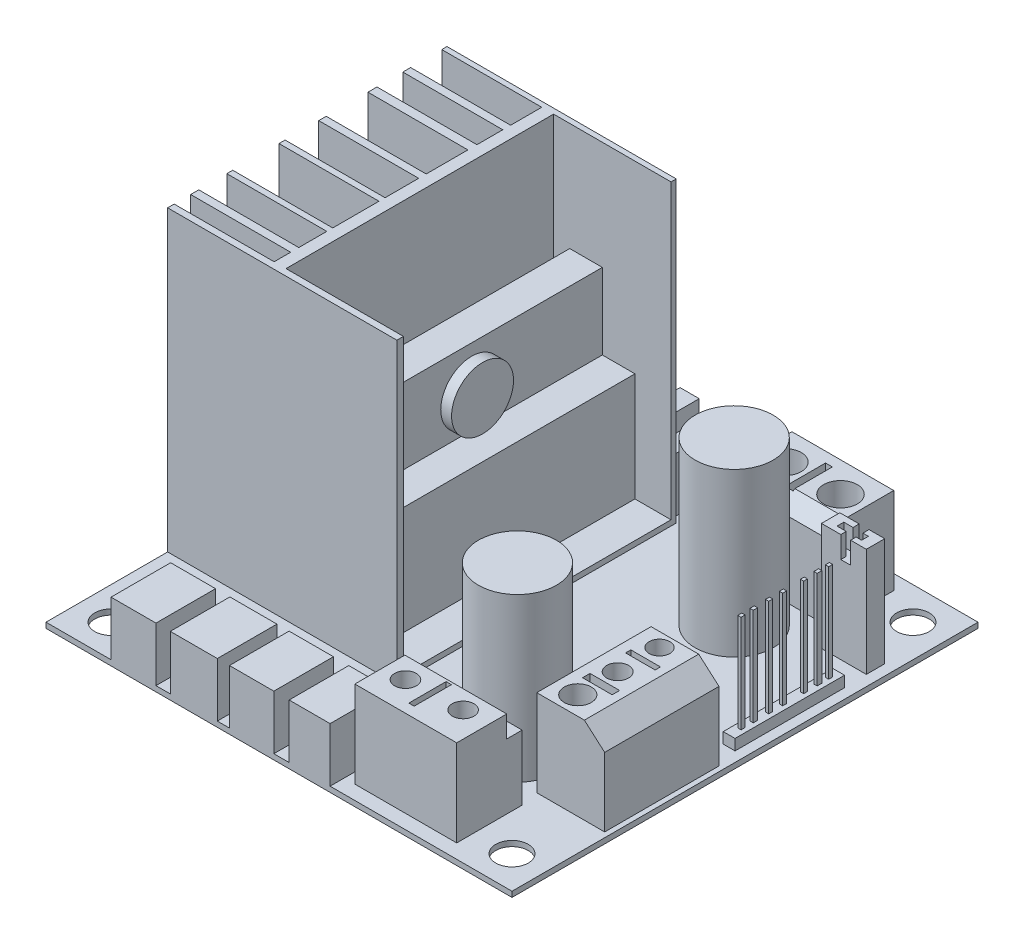
SolidWorks part; units mm, degrees
ref_plane "前视基准面" through (0, 0, 0) normal (0, 0, 1) x (1, 0, 0)
ref_plane "上视基准面" through (0, 0, 0) normal (0, 1, 0) x (1, 0, 0)
ref_plane "右视基准面" through (0, 0, 0) normal (1, 0, 0) x (0, 0, -1)
sketch "草图4" plane through (0, 0, 0) normal (0, 1, 0) x (1, 0, 0)
  line L1 (-21.5, 21.5) -> (21.5, 21.5)
  line L2 (-21.5, 21.5) -> (-21.5, -21.5)
  line L3 (-21.5, -21.5) -> (21.5, -21.5)
  line L4 (21.5, 21.5) -> (21.5, -21.5)
extrude "凸台-拉伸2" add sketch "草图4" along normal blind 0.5
sketch "草图5" plane through (0, 0.5, 0) normal (0, 1, 0) x (1, 0, 0)
  line L0 (-21.5, 21.5) -> (-21.5, -21.5) construction
  line L1 (-21.5, 15.5) -> (-4.3117, 15.5)
  line L2 (-21.5, 15.5) -> (-21.5, -9.2413)
  line L3 (-21.5, -9.2413) -> (-4.3117, -9.2413)
  line L4 (-4.3117, 15.5) -> (-4.3117, -9.2413)
  line L5 (-21.5, -21.5) -> (21.5, -21.5) construction
  line L6 (21.5, 21.5) -> (-21.5, 21.5) construction
  line L7 (21.5, -21.5) -> (21.5, 21.5) construction
  circle A1 centre (-18.5, -18.5) radius 1.5
  circle A2 centre (18.5, 18.5) radius 1.5
  circle A3 centre (-18.5, 18.5) radius 1.5
  circle A4 centre (18.5, -18.5) radius 1.5
  point P14 (18.5, -18.5)
  point P17 (0, 0)
  point P19 (-17.7173, -13.8255)
  dimension "D1" = 37
  dimension "D3" = 3
  dimension "D2" = 37
  dimension "D4" = 3
  dimension "D5" = 3
  dimension "D6" = 3
  dimension "D7" = 3
  dimension "D8" = 3
  dimension "D9" = 3
extrude "切除-拉伸2" cut sketch "草图5" against normal through all contours A3 | A2 | A4 | A1
sketch "草图7" plane through (0, 0.5, 0) normal (0, 1, 0) x (1, 0, 0)
  line L0 (-21.5, 21.5) -> (-21.5, -21.5) construction
  line L1 (-21.5, 15.5) -> (-0.3449, 15.5)
  line L2 (-21.5, 15.5) -> (-21.5, -10.2761)
  line L3 (-21.5, -10.2761) -> (-0.3449, -10.2761)
  line L4 (-0.3449, 15.5) -> (-0.3449, -10.2761)
extrude "凸台-拉伸5" add sketch "草图7" along normal blind 27.5
sketch "草图8" plane through (0, 0.5, 0) normal (0, 1, 0) x (1, 0, 0)
  line L0 (21.5, 21.5) -> (-21.5, 21.5) construction
  line L1 (-15.5, 21.5) -> (4.7141, 21.5)
  line L2 (-15.5, 21.5) -> (-15.5, 16)
  line L3 (-15.5, 16) -> (4.7141, 16)
  line L4 (4.7141, 21.5) -> (4.7141, 16)
sketch "草图9" plane through (0, 0.5, 0) normal (0, 1, 0) x (1, 0, 0)
  line L0 (-21.5, -21.5) -> (21.5, -21.5) construction
  line L1 (-15.5, -21.5) -> (4.7141, -21.5)
  line L2 (-15.5, -21.5) -> (-15.5, -16)
  line L3 (-15.5, -16) -> (4.7141, -16)
  line L4 (4.7141, -21.5) -> (4.7141, -16)
extrude "凸台-拉伸8" add sketch "草图8" along normal blind 5
sketch "草图11" plane through (0, 0.5, 0) normal (0, 1, 0) x (1, 0, 0)
extrude "凸台-拉伸9" add sketch "草图9" along normal blind 5
sketch "草图13" plane through (0, 0.5, 0) normal (0, 1, 0) x (1, 0, 0)
  line L1 (5.6914, -14.1566) -> (15.0908, -14.1566)
  line L2 (5.6914, -14.1566) -> (5.6914, -20.193)
  line L3 (5.6914, -20.193) -> (15.0908, -20.193)
  line L4 (15.0908, -14.1566) -> (15.0908, -20.193)
extrude "凸台-拉伸10" add sketch "草图13" along normal blind 8
sketch "草图14" plane through (0, 0.5, 0) normal (0, 1, 0) x (1, 0, 0)
  line L1 (5.6914, 14.2429) -> (15.0908, 14.2429)
  line L2 (5.6914, 14.2429) -> (5.6914, 20.1355)
  line L3 (5.6914, 20.1355) -> (15.0908, 20.1355)
  line L4 (15.0908, 14.2429) -> (15.0908, 20.1355)
extrude "凸台-拉伸11" add sketch "草图14" along normal blind 8
sketch "草图15" plane through (0, 0.5, 0) normal (0, 1, 0) x (1, 0, 0)
  circle A0 centre (10.5, -10) radius 3.6
extrude "凸台-拉伸13" add sketch "草图15" along normal blind 15
sketch "草图16" plane through (0, 0.5, 0) normal (0, 1, 0) x (1, 0, 0)
  circle A0 centre (10.5, 10) radius 3.6
extrude "凸台-拉伸14" add sketch "草图16" along normal blind 15 contours A0
sketch "草图19" plane through (0, 0.5, 0) normal (0, 1, 0) x (1, 0, 0)
  line L1 (14.7746, -1.9402) -> (21.0409, -1.9402)
  line L2 (14.7746, -1.9402) -> (14.7746, -12.4895)
  line L3 (14.7746, -12.4895) -> (21.0409, -12.4895)
  line L4 (21.0409, -1.9402) -> (21.0409, -12.4895)
extrude "凸台-拉伸15" add sketch "草图19" along normal blind 8
sketch "草图20" plane through (0, 0.5, 0) normal (0, 1, 0) x (1, 0, 0)
  line L1 (16.3843, 13.8692) -> (20.5235, 13.8692)
  line L2 (16.3843, 13.8692) -> (16.3843, 12.1733)
  line L3 (16.3843, 12.1733) -> (20.5235, 12.1733)
  line L4 (20.5235, 13.8692) -> (20.5235, 12.1733)
extrude "凸台-拉伸16" add sketch "草图20" along normal blind 10
sketch "草图21" plane through (0, 0.5, 0) normal (0, 1, 0) x (1, 0, 0)
  line L1 (20.581, 10.1037) -> (19.4887, 10.1037)
  line L2 (20.581, 10.1037) -> (20.581, 0)
  line L3 (20.581, 0) -> (19.4887, 0)
  line L4 (19.4887, 10.1037) -> (19.4887, 0)
extrude "凸台-拉伸17" add sketch "草图21" along normal blind 10
sketch "草图22" plane through (0, 5.5, 0) normal (0, 1, 0) x (1, 0, 0)
  line L0 (4.7141, -16) -> (-15.5, -16) construction
  line L1 (-11.3541, -16) -> (-10.0318, -16)
  line L2 (-11.3541, -16) -> (-11.3541, -21.5)
  line L3 (-11.3541, -21.5) -> (-10.0318, -21.5)
  line L4 (-10.0318, -16) -> (-10.0318, -21.5)
  line L5 (-15.5, -21.5) -> (4.7141, -21.5) construction
extrude "切除-拉伸4" cut sketch "草图22" against normal blind 5
sketch "草图24" plane through (0, 5.5, 0) normal (0, 1, 0) x (1, 0, 0)
  line L0 (4.7141, -16) -> (-10.0318, -16) construction
  line L1 (-5.6914, -16) -> (-4.5704, -16)
  line L2 (-5.6914, -16) -> (-5.6914, -21.5)
  line L3 (-5.6914, -21.5) -> (-4.5704, -21.5)
  line L4 (-4.5704, -16) -> (-4.5704, -21.5)
  line L5 (-10.0318, -21.5) -> (4.7141, -21.5) construction
  line L7 (0, -16) -> (1.0923, -16)
  line L8 (0, -16) -> (0, -21.5)
  line L9 (0, -21.5) -> (1.0923, -21.5)
  line L10 (1.0923, -16) -> (1.0923, -21.5)
extrude "切除-拉伸5" cut sketch "草图24" against normal blind 5 contours L2 L1 L4 L3
sketch "草图26" plane through (0, 5.5, 0) normal (0, 1, 0) x (1, 0, 0)
  line L0 (4.7141, -16) -> (-4.5704, -16) construction
  line L1 (-0.4764, -16) -> (0.9371, -16)
  line L2 (-0.4764, -16) -> (-0.4764, -21.5)
  line L3 (-0.4764, -21.5) -> (0.9371, -21.5)
  line L4 (0.9371, -16) -> (0.9371, -21.5)
  line L5 (-4.5704, -21.5) -> (4.7141, -21.5) construction
extrude "切除-拉伸6" cut sketch "草图26" against normal blind 5
sketch "草图27" plane through (0, 8.5, 0) normal (0, 1, 0) x (1, 0, 0)
  line L0 (5.6914, -14.1566) -> (5.6914, -20.193) construction
  line L1 (5.6914, -15.3068) -> (15.0908, -15.3068)
  line L2 (5.6914, -15.3068) -> (5.6914, -14.1566)
  line L3 (5.6914, -14.1566) -> (15.0908, -14.1566)
  line L4 (15.0908, -15.3068) -> (15.0908, -14.1566)
  line L6 (9.706, -15.7886) -> (10.2003, -15.7886)
  line L7 (9.706, -15.7886) -> (9.706, -19.2272)
  line L8 (9.706, -19.2272) -> (10.2003, -19.2272)
  line L9 (10.2003, -15.7886) -> (10.2003, -19.2272)
  circle A0 centre (7.6767, -17.5079) radius 1
  circle A1 centre (12.9411, -17.5079) radius 1
extrude "切除-拉伸8" cut sketch "草图27" against normal blind 5 contours L7 L6 L9 L8 | A0
sketch "草图29" plane through (0, 8.5, 0) normal (0, 1, 0) x (1, 0, 0)
  circle A0 centre (12.7575, -17.2693) radius 1
extrude "切除-拉伸9" cut sketch "草图29" against normal blind 5
sketch "草图30" plane through (0, 8.5, 0) normal (0, 1, 0) x (1, 0, 0)
  line L0 (5.6914, -14.1566) -> (5.6914, -20.193) construction
  line L1 (5.6914, -15.576) -> (15.0908, -15.576)
  line L2 (5.6914, -15.576) -> (5.6914, -14.1566)
  line L3 (5.6914, -14.1566) -> (15.0908, -14.1566)
  line L4 (15.0908, -15.576) -> (15.0908, -14.1566)
extrude "切除-拉伸10" cut sketch "草图30" against normal blind 2
sketch "草图38" plane through (0, 0, 12.4895) normal (0, 0, 1) x (1, 0, 0)
  line L6 (19.1686, 8.5) -> (21.0409, 6.859)
  line L7 (14.7746, 8.5) -> (21.0409, 8.5) construction
  line L8 (21.0409, 8.5) -> (21.0409, 0.5) construction
  line L9 (21.0409, 6.859) -> (21.0409, 8.5)
  line L10 (21.0409, 8.5) -> (19.1686, 8.5)
extrude "切除-拉伸12" cut sketch "草图38" against normal blind 10.55
sketch "草图39" plane through (0, 8.5, 0) normal (0, 1, 0) x (1, 0, 0)
  line L1 (15.6945, -4.7285) -> (18.4252, -4.7285)
  line L2 (15.6945, -4.7285) -> (15.6945, -5.2171)
  line L3 (15.6945, -5.2171) -> (18.4252, -5.2171)
  line L4 (18.4252, -4.7285) -> (18.4252, -5.2171)
  line L9 (15.6945, -8.494) -> (18.4252, -8.494)
  line L10 (15.6945, -8.494) -> (15.6945, -9.1838)
  line L11 (15.6945, -9.1838) -> (18.4252, -9.1838)
  line L12 (18.4252, -8.494) -> (18.4252, -9.1838)
extrude "切除-拉伸13" cut sketch "草图39" against normal blind 5
sketch "草图40" plane through (0, 8.5, 0) normal (0, 1, 0) x (1, 0, 0)
  circle A0 centre (16.8346, -3.2268) radius 0.9556
  circle A1 centre (16.8346, -7.0856) radius 1.0107
  circle A2 centre (16.8346, -10.7655) radius 1.2457
extrude "切除-拉伸14" cut sketch "草图40" against normal blind 5
sketch "草图42" plane through (0, 28, 0) normal (0, 1, 0) x (1, 0, 0)
  line L0 (-21.5, 15.5) -> (-21.5, -10.2761) construction
  line L1 (-21.5, 15.019) -> (-12.2739, 15.019)
  line L2 (-21.5, 15.019) -> (-21.5, 12.1445)
  line L3 (-21.5, 12.1445) -> (-12.2739, 12.1445)
  line L4 (-12.2739, 15.019) -> (-12.2739, 12.1445)
  line L6 (-21.5, 11.4259) -> (-12.2739, 11.4259)
  line L7 (-21.5, 11.4259) -> (-21.5, 9.0401)
  line L8 (-21.5, 9.0401) -> (-12.2739, 9.0401)
  line L9 (-12.2739, 11.4259) -> (-12.2739, 9.0401)
  line L10 (-21.5, 8.2065) -> (-12.2739, 8.2065)
  line L11 (-21.5, 8.2065) -> (-21.5, 4.3548)
  line L12 (-21.5, 4.3548) -> (-12.2739, 4.3548)
  line L13 (-12.2739, 8.2065) -> (-12.2739, 4.3548)
  line L14 (-21.5, 3.6649) -> (-12.2739, 3.6649)
  line L15 (-21.5, 3.6649) -> (-21.5, 0.5605)
  line L16 (-21.5, 0.5605) -> (-12.2739, 0.5605)
  line L17 (-12.2739, 3.6649) -> (-12.2739, 0.5605)
  line L18 (-21.5, 0) -> (-12.2739, 0)
  line L19 (-21.5, 0) -> (-21.5, -4.2685)
  line L20 (-21.5, -4.2685) -> (-12.2739, -4.2685)
  line L21 (-12.2739, 0) -> (-12.2739, -4.2685)
  line L22 (-21.5, -4.8147) -> (-12.2739, -4.8147)
  line L23 (-21.5, -4.8147) -> (-21.5, -7.4017)
  line L24 (-21.5, -7.4017) -> (-12.2739, -7.4017)
  line L25 (-12.2739, -4.8147) -> (-12.2739, -7.4017)
  line L26 (-21.5, -8.149) -> (-12.2739, -8.149)
  line L27 (-21.5, -8.149) -> (-21.5, -9.6725)
  line L28 (-21.5, -9.6725) -> (-12.2739, -9.6725)
  line L29 (-12.2739, -8.149) -> (-12.2739, -9.6725)
extrude "切除-拉伸15" cut sketch "草图42" against normal blind 27
sketch "草图43" plane through (0, 28, 0) normal (0, 1, 0) x (1, 0, 0)
  line L0 (-0.3449, -10.2761) -> (-0.3449, 15.5) construction
  line L1 (-0.3449, 15.019) -> (-3.6742, 15.019)
  line L2 (-0.3449, 15.019) -> (-0.3449, -9.6725)
  line L3 (-0.3449, -9.6725) -> (-3.6742, -9.6725)
  line L4 (-3.6742, 15.019) -> (-3.6742, -9.6725)
extrude "切除-拉伸16" cut sketch "草图43" against normal blind 27
sketch "草图44" plane through (0, 28, 0) normal (0, 1, 0) x (1, 0, 0)
  line L1 (-11.181, 15.019) -> (-9.6923, 15.019)
  line L2 (-11.181, 15.019) -> (-11.181, -9.6725)
  line L3 (-11.181, -9.6725) -> (-9.6923, -9.6725)
  line L4 (-9.6923, 15.019) -> (-9.6923, -9.6725)
extrude "切除-拉伸17" cut sketch "草图44" against normal blind 27
sketch "草图45" plane through (0, 28, 0) normal (0, 1, 0) x (1, 0, 0)
  line L1 (-9.6923, 15.019) -> (-3.6742, 15.019)
  line L2 (-9.6923, 15.019) -> (-9.6923, -9.6725)
  line L3 (-9.6923, -9.6725) -> (-3.6742, -9.6725)
  line L4 (-3.6742, 15.019) -> (-3.6742, -9.6725)
extrude "切除-拉伸18" cut sketch "草图45" against normal blind 10
sketch "草图46" plane through (0, 18, 0) normal (0, 1, 0) x (1, 0, 0)
  line L0 (-3.6742, 15.019) -> (-9.6923, 15.019) construction
  line L1 (-6.6833, 15.019) -> (-3.6742, 15.019)
  line L2 (-6.6833, 15.019) -> (-6.6833, -9.6725)
  line L3 (-6.6833, -9.6725) -> (-3.6742, -9.6725)
  line L4 (-3.6742, 15.019) -> (-3.6742, -9.6725)
extrude "切除-拉伸20" cut sketch "草图46" against normal blind 7
sketch "草图47" plane through (-6.6833, 0, 0) normal (1, 0, 0) x (0, 0, -1)
  circle A0 centre (2.9642, 14.0726) radius 2.8566
extrude "凸台-拉伸18" add sketch "草图47" along normal blind 1
sketch "草图48" plane through (0, 10.5, 0) normal (0, 1, 0) x (1, 0, 0)
  line L1 (17.3183, 13.3031) -> (19.5822, 13.3031)
  line L2 (17.3183, 13.3031) -> (17.3183, 12.6757)
  line L3 (17.3183, 12.6757) -> (19.5822, 12.6757)
  line L4 (19.5822, 13.3031) -> (19.5822, 12.6757)
extrude "切除-拉伸21" cut sketch "草图48" against normal blind 2
sketch "草图49" plane through (0, 10.5, 0) normal (0, 1, 0) x (1, 0, 0)
  line L0 (19.5822, 13.3031) -> (17.3183, 13.3031) construction
  line L1 (18.166, 13.3031) -> (19.073, 13.3031)
  line L2 (18.166, 13.3031) -> (18.166, 13.8692)
  line L3 (18.166, 13.8692) -> (19.073, 13.8692)
  line L4 (19.073, 13.3031) -> (19.073, 13.8692)
  line L5 (20.5235, 13.8692) -> (16.3843, 13.8692) construction
  line L6 (17.3183, 12.6757) -> (19.5822, 12.6757) construction
  line L7 (18.166, 12.6757) -> (19.073, 12.6757)
  line L8 (18.166, 12.6757) -> (18.166, 12.1733)
  line L9 (18.166, 12.1733) -> (19.073, 12.1733)
  line L10 (19.073, 12.6757) -> (19.073, 12.1733)
  line L11 (16.3843, 12.1733) -> (20.5235, 12.1733) construction
extrude "切除-拉伸22" cut sketch "草图49" against normal blind 2
sketch "草图51" plane through (0, 10.5, 0) normal (0, 1, 0) x (1, 0, 0)
  line L0 (20.581, 10.1037) -> (19.4887, 10.1037) construction
  line L1 (19.8718, 10.1037) -> (19.4887, 10.1037)
  line L2 (19.8718, 10.1037) -> (19.8718, 0)
  line L3 (19.8718, 0) -> (19.4887, 0)
  line L4 (19.4887, 10.1037) -> (19.4887, 0)
  line L5 (19.4887, 0) -> (20.581, 0) construction
  line L6 (20.581, 10.1037) -> (20.1752, 10.1037)
  line L7 (20.581, 10.1037) -> (20.581, 0)
  line L8 (20.581, 0) -> (20.1752, 0)
  line L9 (20.1752, 10.1037) -> (20.1752, 0)
extrude "切除-拉伸24" cut sketch "草图51" against normal blind 9
sketch "草图52" plane through (0, 10.5, 0) normal (0, 1, 0) x (1, 0, 0)
  line L0 (20.1752, 10.1037) -> (20.1752, 0) construction
  line L1 (19.8718, 10.1037) -> (20.1752, 10.1037)
  line L2 (19.8718, 10.1037) -> (19.8718, 9.4124)
  line L3 (19.8718, 9.4124) -> (20.1752, 9.4124)
  line L4 (20.1752, 10.1037) -> (20.1752, 9.4124)
  line L5 (19.8718, 0) -> (19.8718, 10.1037) construction
  line L6 (19.8718, 9.041) -> (20.1752, 9.041)
  line L7 (19.8718, 9.041) -> (19.8718, 8.422)
  line L8 (19.8718, 8.422) -> (20.1752, 8.422)
  line L9 (20.1752, 9.041) -> (20.1752, 8.422)
  line L10 (20.1752, 10.1037) -> (20.1752, 0) construction
  line L11 (19.8718, 0) -> (19.8718, 10.1037) construction
  line L12 (19.8718, 7.9809) -> (20.1752, 7.9809)
  line L13 (19.8718, 7.9809) -> (19.8718, 7.091)
  line L14 (19.8718, 7.091) -> (20.1752, 7.091)
  line L15 (20.1752, 7.9809) -> (20.1752, 7.091)
  line L17 (19.8718, 6.7351) -> (20.1752, 6.7351)
  line L18 (19.8718, 6.7351) -> (19.8718, 5.1721)
  line L19 (19.8718, 5.1721) -> (20.1752, 5.1721)
  line L20 (20.1752, 6.7351) -> (20.1752, 5.1721)
  line L21 (19.8718, 4.8006) -> (20.1752, 4.8006)
  line L22 (19.8718, 4.8006) -> (19.8718, 3.8798)
  line L23 (19.8718, 3.8798) -> (20.1752, 3.8798)
  line L24 (20.1752, 4.8006) -> (20.1752, 3.8798)
  line L25 (19.8718, 3.5162) -> (20.1752, 3.5162)
  line L26 (19.8718, 3.5162) -> (19.8718, 2.4793)
  line L27 (19.8718, 2.4793) -> (20.1752, 2.4793)
  line L28 (20.1752, 3.5162) -> (20.1752, 2.4793)
  line L29 (19.8718, 2.0847) -> (20.1752, 2.0847)
  line L30 (19.8718, 2.0847) -> (19.8718, 1.3341)
  line L31 (19.8718, 1.3341) -> (20.1752, 1.3341)
  line L32 (20.1752, 2.0847) -> (20.1752, 1.3341)
  line L33 (19.8718, 0.9627) -> (20.1752, 0.9627)
  line L34 (19.8718, 0.9627) -> (19.8718, 0)
  line L35 (19.8718, 0) -> (20.1752, 0)
  line L36 (20.1752, 0.9627) -> (20.1752, 0)
extrude "切除-拉伸25" cut sketch "草图52" against normal blind 9
sketch "草图53" plane through (0, 5.5, 0) normal (0, 1, 0) x (1, 0, 0)
  line L0 (4.7141, 21.5) -> (-15.5, 21.5) construction
  line L1 (-13.224, 21.5) -> (-12.4768, 21.5)
  line L2 (-13.224, 21.5) -> (-13.224, 16)
  line L3 (-13.224, 16) -> (-12.4768, 16)
  line L4 (-12.4768, 21.5) -> (-12.4768, 16)
  line L5 (-15.5, 16) -> (4.7141, 16) construction
  line L7 (-10.6171, 21.5) -> (-9.3158, 21.5)
  line L8 (-10.6171, 21.5) -> (-10.6171, 16)
  line L9 (-10.6171, 16) -> (-9.3158, 16)
  line L10 (-9.3158, 21.5) -> (-9.3158, 16)
  line L11 (-7.1203, 21.5) -> (-5.9896, 21.5)
  line L12 (-7.1203, 21.5) -> (-7.1203, 16)
  line L13 (-7.1203, 16) -> (-5.9896, 16)
  line L14 (-5.9896, 21.5) -> (-5.9896, 16)
  line L15 (-4.2235, 21.5) -> (-2.5309, 21.5)
  line L16 (-4.2235, 21.5) -> (-4.2235, 16)
  line L17 (-4.2235, 16) -> (-2.5309, 16)
  line L18 (-2.5309, 21.5) -> (-2.5309, 16)
  line L19 (-0.9148, 21.5) -> (0.7454, 21.5)
  line L20 (-0.9148, 21.5) -> (-0.9148, 16)
  line L21 (-0.9148, 16) -> (0.7454, 16)
  line L22 (0.7454, 21.5) -> (0.7454, 16)
  line L23 (2.2681, 21.5) -> (2.9886, 21.5)
  line L24 (2.2681, 21.5) -> (2.2681, 16)
  line L25 (2.2681, 16) -> (2.9886, 16)
  line L26 (2.9886, 21.5) -> (2.9886, 16)
extrude "切除-拉伸26" cut sketch "草图53" against normal blind 5
sketch "草图54" plane through (0, 8.5, 0) normal (0, 1, 0) x (1, 0, 0)
  line L1 (9.7444, 19.1869) -> (10.3767, 19.1869)
  line L2 (9.7444, 19.1869) -> (9.7444, 15.5651)
  line L3 (9.7444, 15.5651) -> (10.3767, 15.5651)
  line L4 (10.3767, 19.1869) -> (10.3767, 15.5651)
  circle A0 centre (7.7897, 17.376) radius 1.5281
  circle A1 centre (12.935, 17.376) radius 1.5522
extrude "切除-拉伸27" cut sketch "草图54" against normal blind 5
sketch "草图55" plane through (15.0908, 0, 0) normal (1, 0, 0) x (0, 0, -1)
  line L0 (15.7243, 8.5) -> (14.2429, 7.4597)
  line L1 (14.2429, 8.5) -> (20.1355, 8.5) construction
  line L2 (14.2429, 8.5) -> (14.2429, 0.5) construction
  line L3 (14.2429, 7.4597) -> (14.2429, 8.5)
  line L4 (14.2429, 8.5) -> (15.7243, 8.5)
extrude "切除-拉伸28" cut sketch "草图55" against normal up to vertex (10.3767 mm away)
